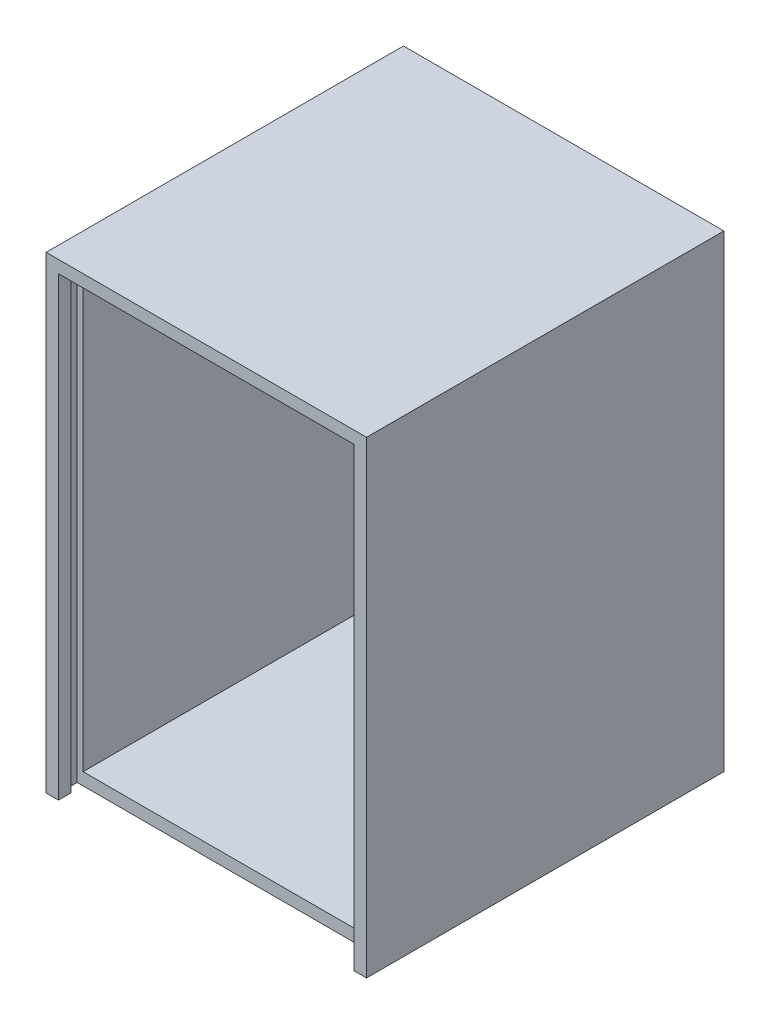
SolidWorks part; units mm, degrees
ref_plane "Front Plane" through (0, 0, 0) normal (0, 0, 1) x (1, 0, 0)
ref_plane "Top Plane" through (0, 0, 0) normal (0, 1, 0) x (1, 0, 0)
ref_plane "Right Plane" through (0, 0, 0) normal (1, 0, 0) x (0, 0, -1)
sketch "Sketch1" plane through (0, 0, 0) normal (0, 0, 1) x (1, 0, 0)
  line L1 (0, 0) -> (130, 0)
  line L2 (0, 0) -> (0, -190)
  line L3 (0, -190) -> (130, -190)
  line L4 (130, 0) -> (130, -190)
  dimension "D1" = 190
  dimension "D2" = 130
extrude "Boss-Extrude1" add sketch "Sketch1" along normal blind 5
sketch "Sketch2" plane through (0, 0, 5) normal (0, 0, 1) x (1, 0, 0)
  line L1 (0, 0) -> (130, 0)
  line L2 (0, 0) -> (0, -190)
  line L3 (0, -190) -> (130, -190)
  line L4 (130, 0) -> (130, -190)
  line L5 (5, -185) -> (125, -185)
  line L6 (5, -185) -> (5, -5)
  line L7 (5, -5) -> (125, -5)
  line L8 (125, -185) -> (125, -5)
  line L9 (5, -185) -> (125, -5) construction
  line L10 (5, -5) -> (125, -185) construction
  point P6 (65, -95)
  dimension "D1" = 120
  dimension "D2" = 180
  dimension "D3" = 5
  dimension "D4" = 5
extrude "Boss-Extrude2" add sketch "Sketch2" along normal blind 130
sketch "Sketch3" plane through (0, 0, 135) normal (0, 0, 1) x (1, 0, 0)
  line L0 (0, -190) -> (0, 0)
  line L1 (0, 0) -> (130, 0)
  line L2 (130, 0) -> (130, -190)
  line L3 (130, -190) -> (125, -190)
  line L4 (0, -190) -> (130, -190) construction
  line L5 (125, -190) -> (125, -185)
  line L6 (125, -185) -> (125, -5)
  line L7 (125, -5) -> (5, -5)
  line L8 (5, -5) -> (5, -190)
  line L9 (5, -190) -> (0, -190)
extrude "Boss-Extrude3" add sketch "Sketch3" along normal blind 10
sketch "Sketch4" plane through (0, -190, 0) normal (0, -1, 0) x (1, 0, 0)
  line L0 (5, 145) -> (5, 135) construction
  line L1 (5, 140) -> (2.6, 140)
  line L2 (5, 140) -> (5, 135)
  line L3 (5, 135) -> (2.6, 135)
  line L4 (2.6, 140) -> (2.6, 135)
  line L5 (0, 145) -> (5, 145) construction
  line L7 (125, 135) -> (127.4, 135)
  line L8 (125, 135) -> (125, 140)
  line L9 (125, 140) -> (127.4, 140)
  line L10 (127.4, 135) -> (127.4, 140)
  dimension "D1" = 2.4
  dimension "D2" = 5
  dimension "D3" = 5
  dimension "D4" = 2.4
extrude "Cut-Extrude1" cut sketch "Sketch4" against normal blind 187.4
sketch "Sketch5" plane through (0, -5, 0) normal (0, -1, 0) x (1, 0, 0)
  line L1 (5, 135) -> (125, 135)
  line L2 (5, 135) -> (5, 140)
  line L3 (5, 140) -> (125, 140)
  line L4 (125, 135) -> (125, 140)
extrude "Cut-Extrude2" cut sketch "Sketch5" against normal blind 2.4
